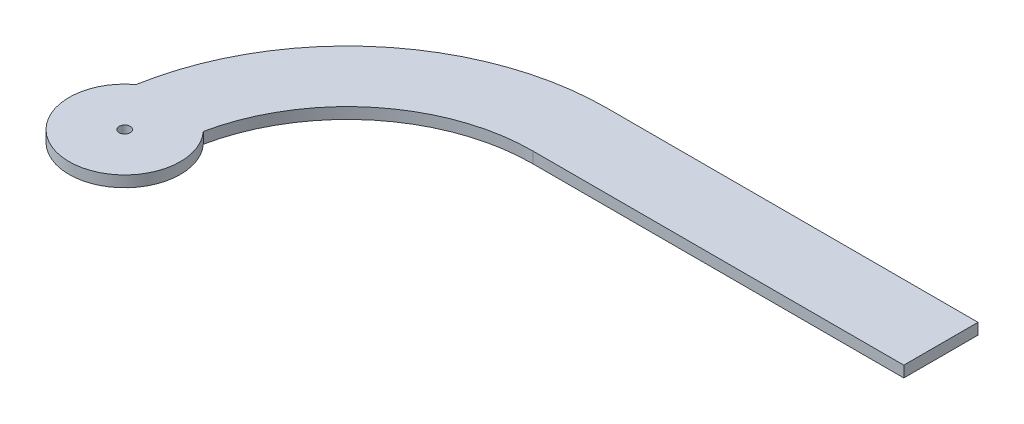
SolidWorks part; units mm, degrees
ref_plane "Front Plane" through (0, 0, 0) normal (0, 0, 1) x (1, 0, 0)
ref_plane "Top Plane" through (0, 0, 0) normal (0, 1, 0) x (1, 0, 0)
ref_plane "Right Plane" through (0, 0, 0) normal (1, 0, 0) x (0, 0, -1)
sketch "Sketch1" plane through (0, 0, 0) normal (0, 1, 0) x (1, 0, 0)
  line L1 (0, 50) -> (100, 50)
  line L2 (100, 50) -> (100, 70)
  line L3 (100, 70) -> (0, 70)
  arc A0 (0, 50) -> (-48.9583, 10.1529) centre (0, 0) ccw
  arc A1 (0, 70) -> (-68.9583, 12.0311) centre (0, 0) ccw
  arc A2 (-68.9583, 12.0311) -> (-48.9583, 10.1529) centre (-60, 0) ccw
  circle A3 centre (-60, 0) radius 1.5
  dimension "D1" = 100
  dimension "D2" = 140
  dimension "D4" = 30
  dimension "D3" = 100
  dimension "D5" = 60
  dimension "D6" = 50
extrude "Boss-Extrude1" add sketch "Sketch1" along normal blind 3
